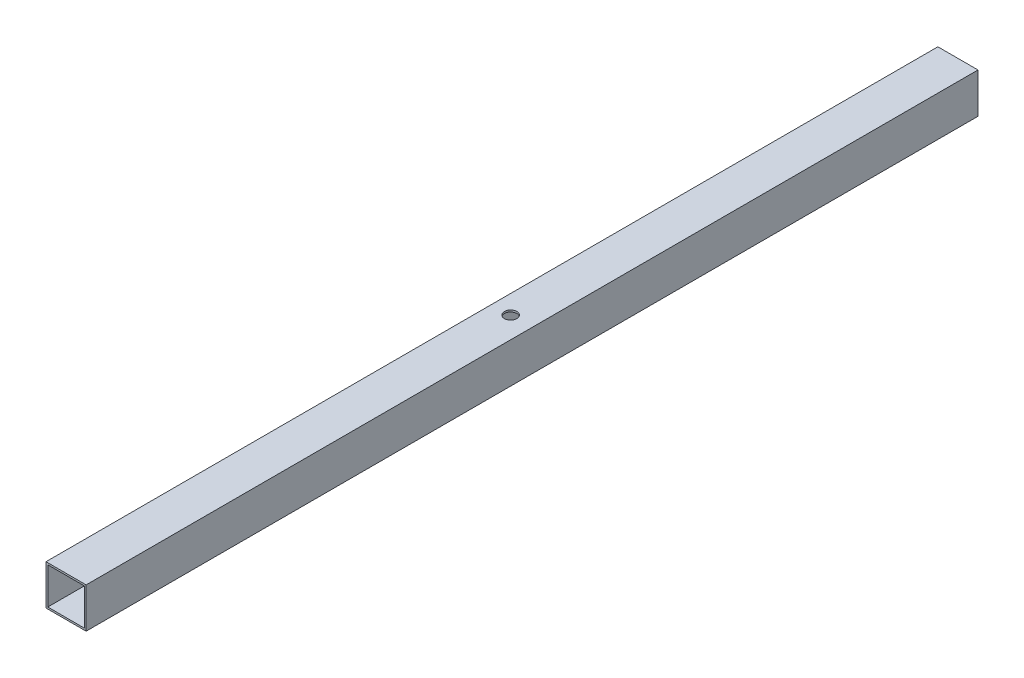
SolidWorks part; units mm, degrees
ref_plane "Alzado" through (0, 0, 0) normal (0, 0, 1) x (1, 0, 0)
ref_plane "Planta" through (0, 0, 0) normal (0, 1, 0) x (1, 0, 0)
ref_plane "Vista lateral" through (0, 0, 0) normal (1, 0, 0) x (0, 0, -1)
sketch "Croquis2" plane through (0, 0, 0) normal (0, 0, 1) x (1, 0, 0)
  line L0 (0, 0) -> (0, 45)
  line L1 (0, 45) -> (45, 45)
  line L2 (45, 45) -> (45, 0)
  line L3 (45, 0) -> (0, 0)
  dimension "D1" = 45
  dimension "D2" = 45
extrude "Saliente-Extruir3" add sketch "Croquis2" along normal blind 1000
sketch "Croquis12" plane through (0, 0, 0) normal (0, 0, -1) x (-1, 0, 0)
  line L0 (-45, 45) -> (0, 45) construction
  line L1 (-43, 43) -> (-2, 43)
  line L2 (-43, 43) -> (-43, 2)
  line L3 (-43, 2) -> (-2, 2)
  line L4 (-2, 43) -> (-2, 2)
  line L5 (0, 0) -> (-45, 0) construction
  line L6 (-45, 0) -> (-45, 45) construction
  line L7 (0, 45) -> (0, 0) construction
  dimension "D1" = 2
  dimension "D2" = 2
  dimension "D3" = 2
  dimension "D4" = 2
extrude "Cortar-Extruir8" cut sketch "Croquis12" against normal through all
sketch "Croquis13" plane through (0, 0, 0) normal (0, -1, 0) x (1, 0, 0)
  line L0 (0, 1000) -> (45, 1000) construction
  line L1 (0, 0) -> (45, 0) construction
  circle A0 centre (22.5, 980) radius 7
  circle A1 centre (22.5, 940) radius 7
  circle A2 centre (22.5, 20) radius 7
  circle A3 centre (22.5, 60) radius 7
  dimension "D1" = 20
  dimension "D2" = 40
  dimension "D3" = 20
  dimension "D4" = 40
extrude "Cortar-Extruir9" cut sketch "Croquis13" against normal blind 1.6
sketch "Croquis14" plane through (0, 0, 0) normal (-1, 0, 0) x (0, 0, 1)
  line L0 (0, 45) -> (0, 0) construction
  line L1 (1000, 0) -> (0, 0) construction
  circle A0 centre (500, 21) radius 7
  dimension "D1" = 500
  dimension "D2" = 21
sketch "Croquis15" plane through (0, 0, 0) normal (0, -1, 0) x (1, 0, 0)
  line L0 (0, 0) -> (45, 0) construction
  line L1 (0, 507) -> (0, 493) construction
  circle A0 centre (21, 500) radius 7
  dimension "D1" = 500
  dimension "D2" = 21
extrude "Cortar-Extruir11" cut sketch "Croquis15" against normal through all
